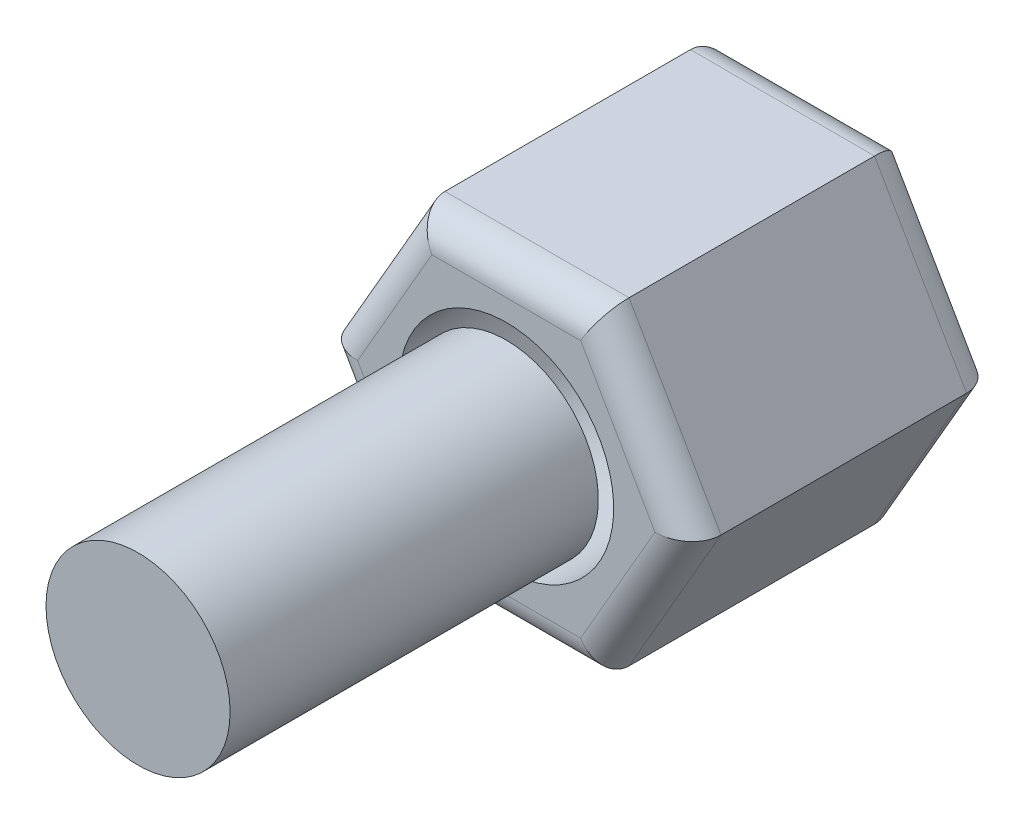
SolidWorks part; units mm, degrees
ref_plane "正面" through (0, 0, 0) normal (0, 0, 1) x (1, 0, 0)
ref_plane "平面" through (0, 0, 0) normal (0, 1, 0) x (1, 0, 0)
ref_plane "右側面" through (0, 0, 0) normal (1, 0, 0) x (0, 0, -1)
sketch "ｽｹｯﾁ1" plane through (0, 0, 0) normal (0, 0, 1) x (1, 0, 0)
  line L1 (3, 0) -> (1.5, 2.5981)
  line L2 (1.5, 2.5981) -> (-1.5, 2.5981)
  line L3 (-1.5, 2.5981) -> (-3, 0)
  line L4 (-3, 0) -> (-1.5, -2.5981)
  line L5 (-1.5, -2.5981) -> (1.5, -2.5981)
  line L6 (1.5, -2.5981) -> (3, 0)
  circle A0 centre (0, 0) radius 2.5981 construction
extrude "ﾎﾞｽ - 押し出し2" add sketch "ｽｹｯﾁ1" along normal blind 5
sketch "ｽｹｯﾁ2" plane through (0, 0, 5) normal (0, 0, 1) x (1, 0, 0)
  circle A0 centre (0, 0) radius 1.5
extrude "ﾎﾞｽ - 押し出し3" add sketch "ｽｹｯﾁ2" along normal blind 6
sketch "ｽｹｯﾁ3" plane through (0, 0, 0) normal (0, 0, -1) x (-1, 0, 0)
  circle A0 centre (0, 0) radius 1.75
extrude "ｶｯﾄ - 押し出し1" cut sketch "ｽｹｯﾁ3" against normal blind 5
fillet "ﾌｨﾚｯﾄ1" radius 0.5 12 edges at (-2.25, 1.299, 0) (0, 2.5981, 0) (2.25, 1.299, 0) (2.25, -1.299, 0) (-2.25, -1.299, 0) (0, -2.5981, 0) (2.25, -1.299, 5) (0, -2.5981, 5) (-2.25, -1.299, 5) (-2.25, 1.299, 5) (0, 2.5981, 5) (2.25, 1.299, 5)
